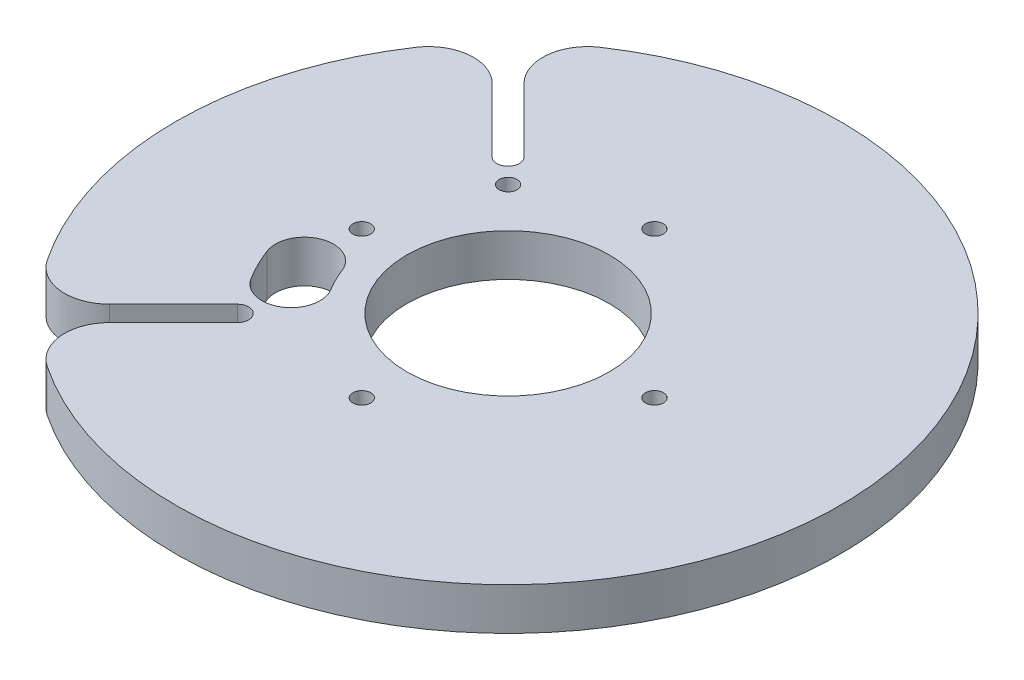
SolidWorks part; units mm, degrees
ref_plane "Front" through (0, 0, 0) normal (0, 0, 1) x (1, 0, 0)
ref_plane "Top" through (0, 0, 0) normal (0, 1, 0) x (1, 0, 0)
ref_plane "Right" through (0, 0, 0) normal (1, 0, 0) x (0, 0, -1)
sketch "Sketch1" plane through (0, 0, 0) normal (0, 1, 0) x (1, 0, 0)
  circle A0 centre (0, 0) radius 75
  dimension "D1" = 150
extrude "Boss-Extrude1" add sketch "Sketch1" along normal blind 9.525
sketch "Sketch2" plane through (0, 9.525, 0) normal (0, 1, 0) x (1, 0, 0)
  circle A0 centre (0, 0) radius 22.098
  dimension "D1" = 44.196
extrude "Cut-Extrude1" [suppressed] cut sketch "Sketch2" against normal through all
hole_wizard "M3 Clearance Hole1" [suppressed] positions "Sketch4" profile "Sketch5" hole size "M3" standard "ANSI Metric"
sketch "Sketch4" plane through (0, 6.35, 0) normal (0, 1, 0) x (1, 0, 0)
  circle A0 centre (0, 0) radius 27 construction
  point P0 (-27, 0)
  point P4 (0, 27)
  point P6 (27, 0)
  point P8 (0, -27)
  dimension "D1" = 54
sketch "Sketch5" plane through (-27, 6.35, 0) normal (1, 0, 0) x (0, 0, 1)
  line L0 (0, 0) -> (0, 6.35)
  line L1 (0, 6.35) -> (1.7, 6.35)
  line L2 (1.7, 6.35) -> (1.7, 0)
  line L5 (1.7, 0) -> (0, 0)
  line L11 (0, -6.35) -> (0, 107.95) construction
  dimension "Thru Hole Dia." = 3.4
  dimension "Thru Hole Depth" = 6.35
hole_wizard "M3 Clearance Slot1" [suppressed] positions "Sketch7" profile "Sketch6" size "M3" standard "ANSI Metric"
sketch "Sketch7" plane through (0, 0, 0) normal (0, -1, 0) x (-1, 0, 0)
  line L0 (55, -30) -> (25, -30) construction
  line L1 (0, 0) -> (52.8466, 0) construction
  arc A1 (53.3, -31.7) -> (53.3, -28.3) centre (53.3, -30) ccw construction
  arc A2 (26.7, -28.3) -> (26.7, -31.7) centre (26.7, -30) ccw construction
  point P0 (40, -30)
sketch "Sketch6" plane through (-40, 0, 30) normal (1, 0, 0) x (0, 0, -1)
  line L0 (0, 0) -> (0, 26.4215)
  line L1 (0, 26.4215) -> (1.7, 25.4)
  line L2 (1.7, 25.4) -> (1.7, 0)
  line L5 (1.7, 0) -> (0, 0)
  line L10 (0, 26.4215) -> (-1.7, 25.4) construction
  line L11 (0, -6.35) -> (0, 107.95) construction
  dimension "Hole Dia." = 3.4
  dimension "Hole Depth" = 25.4
  dimension "Drill Angle" = 118
hole_wizard "M3 Clearance Hole2" [suppressed] positions "Sketch9" profile "Sketch8" hole size "M3" standard "ANSI Metric"
sketch "Sketch9" plane through (0, 6.35, 0) normal (0, 1, 0) x (1, 0, 0)
  point P0 (-53.3, 30)
sketch "Sketch8" plane through (-53.3, 6.35, -30) normal (1, 0, 0) x (0, 0, 1)
  line L0 (0, 0) -> (0, 6.35)
  line L1 (0, 6.35) -> (1.7, 6.35)
  line L2 (1.7, 6.35) -> (1.7, 0)
  line L5 (1.7, 0) -> (0, 0)
  line L11 (0, -6.35) -> (0, 107.95) construction
  dimension "Thru Hole Dia." = 3.4
  dimension "Thru Hole Depth" = 6.35
sketch "Sketch11" plane through (0, 9.525, 0) normal (0, 1, 0) x (1, 0, 0)
  line L0 (-75, 0) -> (75, 0) construction
  line L1 (0, 0) -> (-53.033, 53.033) construction
  line L2 (-54.7986, 51.2065) -> (-32.348, 28.7559)
  line L3 (-51.2065, 54.7986) -> (-28.7559, 32.348)
  line L4 (-51.2065, -54.7986) -> (-28.7559, -32.348)
  line L5 (-54.7986, -51.2065) -> (-32.348, -28.7559)
  circle A0 centre (0, 0) radius 75 construction
  arc A1 (-32.348, 28.7559) -> (-28.7559, 32.348) centre (-30.5519, 30.5519) ccw
  arc A2 (-32.348, -28.7559) -> (-28.7559, -32.348) centre (-30.5519, -30.5519) cw
  arc A3 (-54.7986, 51.2065) -> (-51.2065, 54.7986) centre (0, 0) cw
  arc A4 (-54.7986, -51.2065) -> (-51.2065, -54.7986) centre (0, 0) ccw
  dimension "D1" = 45
  dimension "D2" = 31.75
  dimension "D3" = 5.08
extrude "Cut-Extrude2" cut sketch "Sketch11" against normal up to next
fillet "Fillet1" radius 10.16 4 edges at (-51.2065, 4.7625, 54.7986) (-54.7986, 4.7625, 51.2065) (-54.7986, 4.7625, -51.2065) (-51.2065, 4.7625, -54.7986)
extrude "Cut-Extrude26" [suppressed] cut sketch "Sketch35" against normal through all
sketch "Sketch35" plane through (-73.7688, 9.525, -121.0804) normal (0, 1, 0) x (1, 0, 0)
  circle A1 centre (48.605, -95.9166) radius 2.0193 construction
  circle A3 centre (73.7688, -121.0804) radius 22.86 construction
  circle A4 centre (73.7688, -121.0804) radius 35.587 construction
  arc A5 (40.7129, -134.2614) -> (42.8303, -138.6656) centre (73.7688, -121.0804) ccw construction
  arc A6 (33.7184, -137.0504) -> (36.2838, -142.3866) centre (73.7688, -121.0804) ccw
  arc A7 (47.7074, -131.4723) -> (49.3768, -134.9446) centre (73.7688, -121.0804) ccw
  arc A8 (47.7074, -131.4723) -> (33.7184, -137.0504) centre (40.7129, -134.2614) ccw
  arc A9 (36.2838, -142.3866) -> (49.3768, -134.9446) centre (42.8303, -138.6656) ccw
  point P9 (41.6959, -136.4999)
extrude "Cut-Extrude30" cut sketch "Sketch39" against normal through all
sketch "Sketch39" plane through (-73.7688, 9.525, -121.0804) normal (0, 1, 0) x (1, 0, 0)
  line L0 (73.7688, -121.0804) -> (73.7688, -88.0604) construction
  circle A1 centre (73.7688, -121.0804) radius 77.46 construction
  circle A2 centre (73.7688, -121.0804) radius 22.86
  circle A3 centre (73.7688, -88.0604) radius 2.0193
  circle A4 centre (106.7888, -121.0804) radius 2.0193
  circle A5 centre (73.7688, -154.1004) radius 2.0193
  circle A6 centre (40.7488, -121.0804) radius 2.0193
  point P4 (73.7688, -98.2204)
  point P16 (73.7688, -121.0804)
extrude "Cut-Extrude33" cut sketch "Sketch42" against normal through all
sketch "Sketch42" plane through (-73.7688, 9.525, -121.0804) normal (0, 1, 0) x (1, 0, 0)
  line L0 (43.2169, -90.5284) -> (48.605, -95.9166) construction
  arc A1 (41.4208, -92.3245) -> (45.0129, -88.7324) centre (43.2169, -90.5284) ccw construction
  circle A2 centre (48.605, -95.9166) radius 2.0193
extrude "Cut-Extrude35" cut sketch "Sketch44" against normal through all
sketch "Sketch44" plane through (-73.7688, 9.525, -121.0804) normal (0, 1, 0) x (1, 0, 0)
  circle A2 centre (73.7688, -121.0804) radius 22.86 construction
  circle A3 centre (48.605, -95.9166) radius 2.0193 construction
  circle A4 centre (73.7688, -121.0804) radius 35.587 construction
  arc A5 (40.5263, -133.7834) -> (43.5223, -139.8309) centre (73.7688, -121.0804) ccw construction
  arc A6 (34.406, -136.1222) -> (37.9536, -143.283) centre (73.7688, -121.0804) ccw
  arc A7 (46.6466, -131.4446) -> (49.091, -136.3787) centre (73.7688, -121.0804) ccw
  arc A8 (46.6466, -131.4446) -> (34.406, -136.1222) centre (40.5263, -133.7834) ccw
  arc A9 (37.9536, -143.283) -> (49.091, -136.3787) centre (43.5223, -139.8309) ccw
  point P9 (41.8806, -136.8783)
